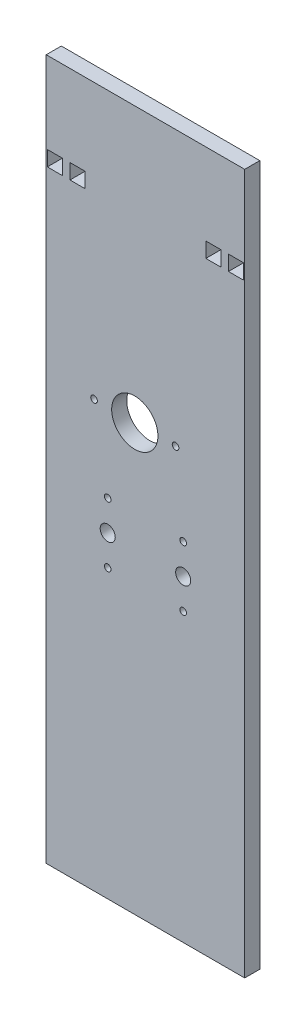
SolidWorks part; units mm, degrees
ref_plane "Front Plane" through (0, 0, 0) normal (0, 0, 1) x (1, 0, 0)
ref_plane "Top Plane" through (0, 0, 0) normal (0, 1, 0) x (1, 0, 0)
ref_plane "Right Plane" through (0, 0, 0) normal (1, 0, 0) x (0, 0, -1)
sketch "Sketch1" plane through (0, 0, 0) normal (0, 0, 1) x (1, 0, 0)
  line B0 (0, 0) -> (96.2, 0)
  line B1 (96.2, 0) -> (96.2, 294.64)
  line B2 (96.2, 294.64) -> (0, 294.64)
  line B3 (0, 294.64) -> (0, 0)
  line B4 (89.375, 254) -> (83.025, 254)
  line B5 (89.375, 260.35) -> (89.375, 254)
  line B6 (83.025, 260.35) -> (89.375, 260.35)
  line B7 (83.025, 254) -> (83.025, 260.35)
  line B8 (79.85, 260.35) -> (79.85, 254)
  line B9 (73.5, 260.35) -> (79.85, 260.35)
  line B10 (73.5, 254) -> (73.5, 260.35)
  line B11 (79.85, 254) -> (73.5, 254)
  line B12 (22.7, 254) -> (16.35, 254)
  line B13 (22.7, 260.35) -> (22.7, 254)
  line B14 (16.35, 260.35) -> (22.7, 260.35)
  line B15 (16.35, 254) -> (16.35, 260.35)
  line B16 (6.825, 254) -> (6.825, 260.35)
  line B17 (6.825, 260.35) -> (13.175, 260.35)
  line B18 (13.175, 260.35) -> (13.175, 254)
  line B19 (13.175, 254) -> (6.825, 254)
  circle B20 centre (63.975, 120.65) radius 1.3891
  circle B21 centre (63.975, 133.35) radius 3.175
  circle B22 centre (63.975, 146.05) radius 1.3891
  circle B23 centre (32.225, 146.05) radius 1.3891
  circle B24 centre (32.225, 133.35) radius 3.175
  circle B25 centre (32.225, 120.65) radius 1.3891
  circle B26 centre (60.755, 179.2092) radius 1.3891
  circle B27 centre (26.465, 179.2092) radius 1.3891
  circle B28 centre (43.61, 179.2092) radius 9.7282
sketch_block_instance "Base-1"
sketch_block "Base"
extrude "Boss-Extrude1" add sketch "Sketch1" along normal blind 6.35
sketch "Sketch2" plane through (0, 0, 6.35) normal (0, 0, 1) x (1, 0, 0)
  line L0 (0, 294.64) -> (0, 0) construction
  line L1 (0, 0) -> (96.2, 0) construction
  line L2 (96.2, 0) -> (96.2, 294.64) construction
  line L3 (3.175, 288.29) -> (3.175, 6.35) construction
  line L4 (93.025, 288.29) -> (93.025, 6.35) construction
  line L5 (96.2, 294.64) -> (0, 294.64) construction
  circle A0 centre (3.175, 6.35) radius 1.7859
  circle A1 centre (93.025, 6.35) radius 1.7859
  circle A2 centre (3.175, 288.29) radius 1.7859
  circle A3 centre (93.025, 288.29) radius 1.7859
  circle A4 centre (3.175, 147.32) radius 1.7859
  circle A5 centre (93.025, 147.32) radius 1.7859
  dimension "D1" = 3.5719
  dimension "D4" = 3.5719
  dimension "D7" = 3.5719
  dimension "D8" = 3.5719
  dimension "D10" = 3.5719
  dimension "D11" = 3.5719
  dimension "D2" = 3.175
  dimension "D3" = 6.35
  dimension "D5" = 3.175
  dimension "D6" = 6.35
  dimension "D9" = 6.35
extrude "Cut-Extrude1" [suppressed] cut sketch "Sketch2" against normal up to next
sketch "Sketch3" plane through (0, 0, 0) normal (-1, 0, 0) x (0, 0, 1)
  line L4 (0, 294.64) -> (0, 0)
  line L5 (0, 0) -> (6.35, 0)
  line L6 (6.35, 0) -> (6.35, 294.64)
  line L7 (6.35, 294.64) -> (0, 294.64)
  line L8 (0, 294.64) -> (0, 0)
  line L9 (0, 0) -> (6.35, 0)
  line L10 (6.35, 0) -> (6.35, 294.64)
  line L11 (6.35, 294.64) -> (0, 294.64)
  dimension "D1" = 0
extrude "Cut-Extrude2" cut sketch "Sketch3" against normal blind 6.35
sketch "Sketch4" plane through (96.2, 0, 0) normal (1, 0, 0) x (0, 0, -1)
  line L4 (0, 0) -> (0, 294.64)
  line L5 (0, 294.64) -> (-6.35, 294.64)
  line L6 (-6.35, 294.64) -> (-6.35, 0)
  line L7 (-6.35, 0) -> (0, 0)
  line L8 (0, 0) -> (0, 294.64)
  line L9 (0, 294.64) -> (-6.35, 294.64)
  line L10 (-6.35, 294.64) -> (-6.35, 0)
  line L11 (-6.35, 0) -> (0, 0)
  dimension "D1" = 0
extrude "Cut-Extrude3" cut sketch "Sketch4" against normal blind 6.35
